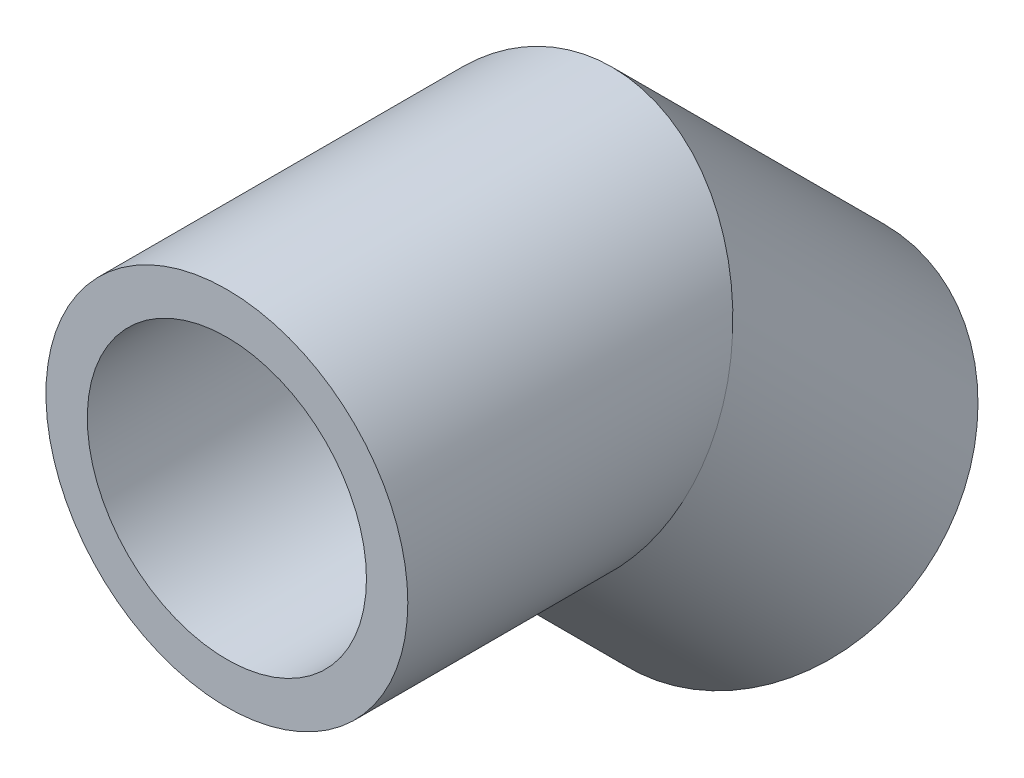
SolidWorks part; units mm, degrees
material "PVC Rigid"
ref_plane "Front Plane" through (0, 0, 0) normal (0, 0, 1) x (1, 0, 0)
ref_plane "Top Plane" through (0, 0, 0) normal (0, 1, 0) x (1, 0, 0)
ref_plane "Right Plane" through (0, 0, 0) normal (1, 0, 0) x (0, 0, -1)
sketch3d "3DSketch1"
  line L0 (0, 0, 0) -> (0, 0, -30)
  line L1 (0, 0, -30) -> (0, -21.2132, -51.2132)
  point P4 (0, 0, 0)
  point P5 (0, 0, 0)
  dimension "D1" = 135
  dimension "D3" = 30
  dimension "D2" = 30
sketch "Sketch1" plane through (0, 0, 0) normal (0, 0, 1) x (1, 0, 0)
  circle A0 centre (0, 0) radius 13.5
  circle A1 centre (0, 0) radius 17.5
  dimension "D1" = 27
  dimension "D2" = 35
sweep "Sweep1" add profiles "Sketch1" path "3DSketch1"
